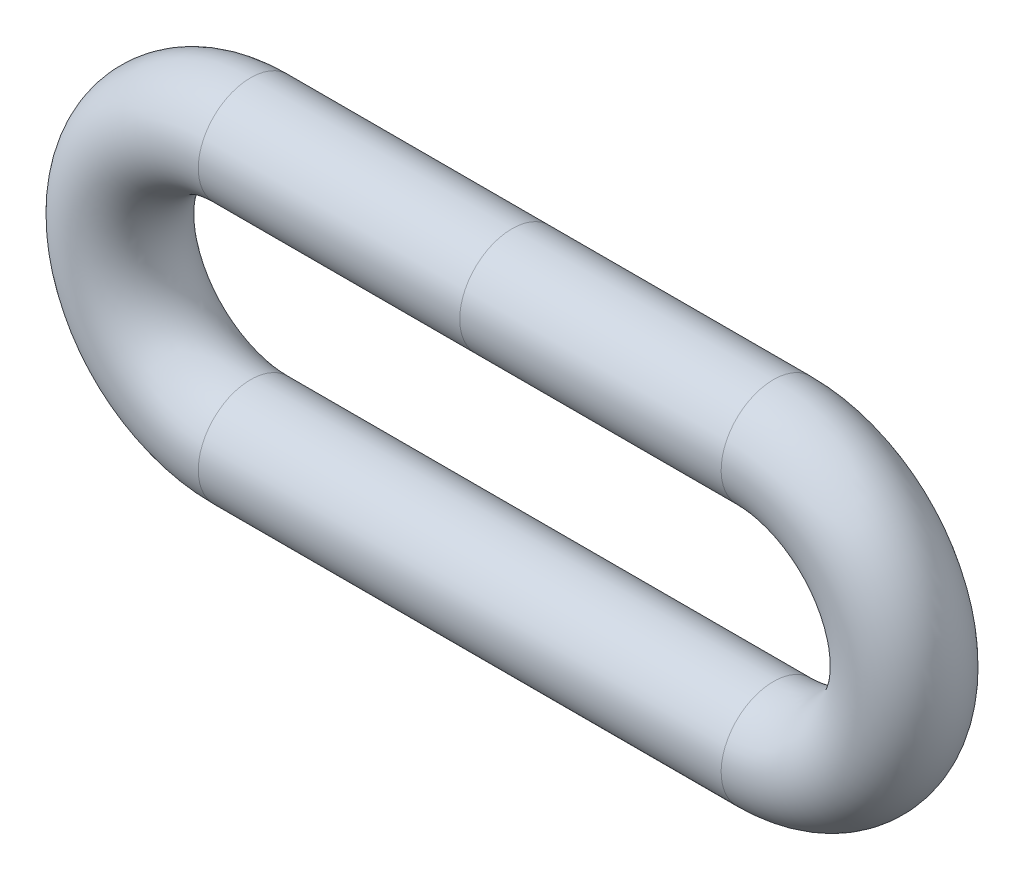
SolidWorks part; units mm, degrees
ref_plane "Front Plane" through (0, 0, 0) normal (0, 0, 1) x (1, 0, 0)
ref_plane "Top Plane" through (0, 0, 0) normal (0, 1, 0) x (1, 0, 0)
ref_plane "Right Plane" through (0, 0, 0) normal (1, 0, 0) x (0, 0, -1)
sketch "Sketch1" plane through (0, 0, 0) normal (0, 0, 1) x (1, 0, 0)
  line L0 (-5, 0) -> (5, 0) construction
  line L1 (-5, 2.5) -> (5, 2.5)
  line L2 (-5, -2.5) -> (5, -2.5)
  arc A0 (-5, 2.5) -> (-5, -2.5) centre (-5, 0) ccw
  arc A1 (5, -2.5) -> (5, 2.5) centre (5, 0) ccw
  point P2 (0, 0)
  dimension "D1" = 10
  dimension "D2" = 5
sketch "Sketch3" plane through (0, 0, 0) normal (1, 0, 0) x (0, 0, -1)
  line L0 (0, 2.5) -> (0, -2.5) construction
  line L1 (0, 2.5) -> (0, -2.5) construction
  circle A0 centre (0, 2.5) radius 1
  dimension "D1" = 2
sweep "Sweep1" add profiles "Sketch3" path "Sketch1"
